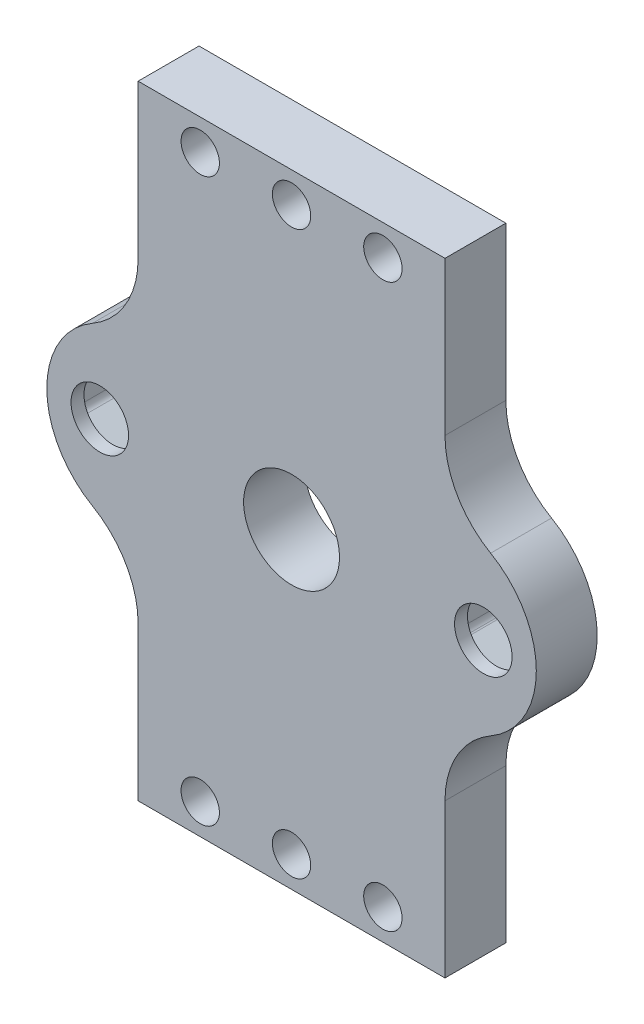
SolidWorks part; units mm, degrees
ref_plane "Front Plane" through (0, 0, 0) normal (0, 0, 1) x (1, 0, 0)
ref_plane "Top Plane" through (0, 0, 0) normal (0, 1, 0) x (1, 0, 0)
ref_plane "Right Plane" through (0, 0, 0) normal (1, 0, 0) x (0, 0, -1)
sketch "Sketch1" plane through (0, 0, 0) normal (0, 0, 1) x (1, 0, 0)
  line L0 (16, 32.5) -> (16, 16.4978)
  line L1 (-16, 16.4978) -> (-16, 32.5)
  line L2 (-16, 32.5) -> (16, 32.5)
  line L3 (16, -32.5) -> (-16, -32.5)
  line L4 (16, -16.4978) -> (16, -32.5)
  line L5 (-16, -32.5) -> (-16, -16.4978)
  arc A0 (20.7625, -8.2489) -> (20.7625, 8.2489) centre (16, 0) ccw
  arc A1 (16, 16.4978) -> (20.7625, 8.2489) centre (25.525, 16.4978) ccw
  circle A2 centre (9.525, 29.325) radius 2
  circle A3 centre (0, 29.325) radius 2
  circle A4 centre (-9.525, 29.325) radius 2
  arc A5 (-20.7625, 8.2489) -> (-16, 16.4978) centre (-25.525, 16.4978) ccw
  arc A6 (20.7625, -8.2489) -> (16, -16.4978) centre (25.525, -16.4978) ccw
  arc A7 (-16, -16.4978) -> (-20.7625, -8.2489) centre (-25.525, -16.4978) ccw
  arc A8 (-20.7625, 8.2489) -> (-20.7625, -8.2489) centre (-16, 0) ccw
  circle A9 centre (-20, 0) radius 3
  circle A10 centre (20, 0) radius 3
  circle A11 centre (0, 0) radius 5
  circle A12 centre (0, -29.325) radius 2
  circle A13 centre (-9.525, -29.325) radius 2
  circle A14 centre (9.525, -29.325) radius 2
extrude "Boss-Extrude1" add sketch "Sketch1" along normal blind 6.35
sketch "Sketch2" plane through (0, 0, 0) normal (0, 0, -1) x (-1, 0, 0)
  line L0 (-24.2999, -1.9872) -> (-24.2999, 1.9857)
  line L1 (-20.4296, -4.7179) -> (-23.8702, -2.7314)
  line L2 (-16.1296, -2.7314) -> (-19.5702, -4.7179)
  line L3 (-15.6999, 1.9857) -> (-15.6999, -1.9872)
  line L4 (-19.5702, 4.7164) -> (-16.1302, 2.7303)
  line L5 (-23.8702, 2.73) -> (-20.4296, 4.7164)
  line L6 (-19.9999, 4.8314) -> (-19.9999, -0.0007) construction
  line L7 (-19.9999, -0.0007) -> (-19.9999, -4.8329) construction
  line L8 (0, 32.5) -> (0, -32.5) construction
  line L9 (16, 32.5) -> (-16, 32.5) construction
  line L10 (-16, -32.5) -> (16, -32.5) construction
  line L11 (15.6999, 1.9857) -> (15.6999, -1.9872)
  line L12 (19.9999, 4.8314) -> (19.9999, -0.0007) construction
  line L13 (19.9999, -0.0007) -> (19.9999, -4.8329) construction
  line L14 (16.1296, -2.7314) -> (19.5702, -4.7179)
  line L15 (20.4296, -4.7179) -> (23.8702, -2.7314)
  line L16 (24.2999, -1.9872) -> (24.2999, 1.9857)
  line L17 (23.8702, 2.73) -> (20.4296, 4.7164)
  line L18 (19.5702, 4.7164) -> (16.1302, 2.7303)
  arc A0 (-15.9999, 2.6381) -> (-16.1302, 2.7303) centre (-16.5633, 1.98) ccw
  arc A1 (15.9999, 2.6381) -> (16.1302, 2.7303) centre (16.5633, 1.98) cw
  spline S0 degree 3 poles (-23.8702, -2.7314) (-23.8703, -2.7314) (-23.8704, -2.7313) (-23.8705, -2.7312) (-23.8915, -2.7191) (-23.9127, -2.7057) (-23.9338, -2.6908) (-24.0382, -2.6176) (-24.1224, -2.5247) (-24.247, -2.3089) (-24.2853, -2.1895) (-24.2966, -2.0626) (-24.2988, -2.0368) (-24.2998, -2.0118) (-24.2999, -1.9875) (-24.2999, -1.9874) (-24.2999, -1.9873) (-24.2999, -1.9872) knots -0.293601 -0.293601 -0.293601 -0.293601 -0.293567 -0.293567 -0.293567 -0.288728 -0.288728 -0.288728 -0.264902 -0.264902 -0.241075 -0.241075 -0.241075 -0.236237 -0.236237 -0.236237 -0.236203 -0.236203 -0.236203 -0.236203 weights 1 1 1 1 1 1 1 1 1 1 1 1 1 1 1 1 1 1
  spline S1 degree 3 poles (-19.5702, -4.7179) (-19.5703, -4.7179) (-19.5704, -4.718) (-19.5705, -4.718) (-19.5915, -4.7301) (-19.6137, -4.7418) (-19.6372, -4.7527) (-19.7527, -4.8064) (-19.8753, -4.8329) (-20.1245, -4.8329) (-20.2471, -4.8064) (-20.3626, -4.7527) (-20.3861, -4.7418) (-20.4083, -4.7301) (-20.4293, -4.718) (-20.4294, -4.718) (-20.4295, -4.7179) (-20.4296, -4.7179) knots -0.293601 -0.293601 -0.293601 -0.293601 -0.293567 -0.293567 -0.293567 -0.288728 -0.288728 -0.288728 -0.264902 -0.264902 -0.241075 -0.241075 -0.241075 -0.236237 -0.236237 -0.236237 -0.236203 -0.236203 -0.236203 -0.236203 weights 1 1 1 1 1 1 1 1 1 1 1 1 1 1 1 1 1 1
  spline S2 degree 3 poles (-15.6999, -1.9872) (-15.6999, -1.9873) (-15.6999, -1.9874) (-15.6999, -1.9875) (-15.7, -2.0118) (-15.701, -2.0368) (-15.7032, -2.0626) (-15.7145, -2.1895) (-15.7528, -2.3089) (-15.8637, -2.5009) (-15.9255, -2.5759) (-15.9999, -2.6396) knots -0.293601 -0.293601 -0.293601 -0.293601 -0.293567 -0.293567 -0.293567 -0.288728 -0.288728 -0.288728 -0.264902 -0.264902 -0.246329 -0.246329 -0.246329 -0.246329 weights 1 1 1 1 1 1 1 1 1 1 1 1
  spline S3 degree 3 poles (-15.9999, 2.6381) (-15.9255, 2.5745) (-15.8637, 2.4994) (-15.7528, 2.3075) (-15.7145, 2.1881) (-15.7032, 2.0611) (-15.701, 2.0354) (-15.7, 2.0103) (-15.6999, 1.9861) (-15.6999, 1.9859) (-15.6999, 1.9858) (-15.6999, 1.9857) knots -0.283475 -0.283475 -0.283475 -0.283475 -0.264902 -0.264902 -0.241075 -0.241075 -0.241075 -0.236237 -0.236237 -0.236237 -0.236203 -0.236203 -0.236203 -0.236203 weights 1 1 1 1 1 1 1 1 1 1 1 1
  spline S4 degree 3 poles (-20.4296, 4.7164) (-20.4295, 4.7165) (-20.4294, 4.7165) (-20.4293, 4.7166) (-20.4083, 4.7287) (-20.3861, 4.7403) (-20.3626, 4.7512) (-20.2471, 4.805) (-20.1245, 4.8314) (-19.8753, 4.8314) (-19.7527, 4.805) (-19.6372, 4.7512) (-19.6137, 4.7403) (-19.5915, 4.7287) (-19.5705, 4.7166) (-19.5704, 4.7165) (-19.5703, 4.7165) (-19.5702, 4.7164) knots -0.293601 -0.293601 -0.293601 -0.293601 -0.293567 -0.293567 -0.293567 -0.288728 -0.288728 -0.288728 -0.264902 -0.264902 -0.241075 -0.241075 -0.241075 -0.236237 -0.236237 -0.236237 -0.236203 -0.236203 -0.236203 -0.236203 weights 1 1 1 1 1 1 1 1 1 1 1 1 1 1 1 1 1 1
  spline S5 degree 3 poles (-24.2999, 1.9857) (-24.2999, 1.9858) (-24.2999, 1.9859) (-24.2999, 1.9861) (-24.2998, 2.0103) (-24.2988, 2.0354) (-24.2966, 2.0611) (-24.2853, 2.1881) (-24.247, 2.3075) (-24.1224, 2.5232) (-24.0382, 2.6162) (-23.9338, 2.6894) (-23.9127, 2.7042) (-23.8915, 2.7176) (-23.8705, 2.7298) (-23.8704, 2.7298) (-23.8703, 2.7299) (-23.8702, 2.73) knots -0.293601 -0.293601 -0.293601 -0.293601 -0.293567 -0.293567 -0.293567 -0.288728 -0.288728 -0.288728 -0.264902 -0.264902 -0.241075 -0.241075 -0.241075 -0.236237 -0.236237 -0.236237 -0.236203 -0.236203 -0.236203 -0.236203 weights 1 1 1 1 1 1 1 1 1 1 1 1 1 1 1 1 1 1
  spline S6 degree 3 poles (-15.9999, -2.6396) (-16.0209, -2.6576) (-16.043, -2.6747) (-16.066, -2.6908) (-16.0871, -2.7057) (-16.1083, -2.7191) (-16.1293, -2.7312) (-16.1294, -2.7313) (-16.1295, -2.7314) (-16.1296, -2.7314) knots -0.246329 -0.246329 -0.246329 -0.246329 -0.241075 -0.241075 -0.241075 -0.236237 -0.236237 -0.236237 -0.236203 -0.236203 -0.236203 -0.236203 weights 1 1 1 1 1 1 1 1 1 1
  spline S7 degree 3 poles (15.6999, -1.9872) (15.6999, -1.9873) (15.6999, -1.9874) (15.6999, -1.9875) (15.7, -2.0118) (15.701, -2.0368) (15.7032, -2.0626) (15.7145, -2.1895) (15.7528, -2.3089) (15.8637, -2.5009) (15.9255, -2.5759) (15.9999, -2.6396) knots -0.293601 -0.293601 -0.293601 -0.293601 -0.293567 -0.293567 -0.293567 -0.288728 -0.288728 -0.288728 -0.264902 -0.264902 -0.246329 -0.246329 -0.246329 -0.246329 weights 1 1 1 1 1 1 1 1 1 1 1 1
  spline S8 degree 3 poles (15.9999, -2.6396) (16.0209, -2.6576) (16.043, -2.6747) (16.066, -2.6908) (16.0871, -2.7057) (16.1083, -2.7191) (16.1293, -2.7312) (16.1294, -2.7313) (16.1295, -2.7314) (16.1296, -2.7314) knots -0.246329 -0.246329 -0.246329 -0.246329 -0.241075 -0.241075 -0.241075 -0.236237 -0.236237 -0.236237 -0.236203 -0.236203 -0.236203 -0.236203 weights 1 1 1 1 1 1 1 1 1 1
  spline S9 degree 3 poles (15.9999, 2.6381) (15.9255, 2.5745) (15.8637, 2.4994) (15.7528, 2.3075) (15.7145, 2.1881) (15.7032, 2.0611) (15.701, 2.0354) (15.7, 2.0103) (15.6999, 1.9861) (15.6999, 1.9859) (15.6999, 1.9858) (15.6999, 1.9857) knots -0.283475 -0.283475 -0.283475 -0.283475 -0.264902 -0.264902 -0.241075 -0.241075 -0.241075 -0.236237 -0.236237 -0.236237 -0.236203 -0.236203 -0.236203 -0.236203 weights 1 1 1 1 1 1 1 1 1 1 1 1
  spline S10 degree 3 poles (19.5702, -4.7179) (19.5703, -4.7179) (19.5704, -4.718) (19.5705, -4.718) (19.5915, -4.7301) (19.6137, -4.7418) (19.6372, -4.7527) (19.7527, -4.8064) (19.8753, -4.8329) (20.1245, -4.8329) (20.2471, -4.8064) (20.3626, -4.7527) (20.3861, -4.7418) (20.4083, -4.7301) (20.4293, -4.718) (20.4294, -4.718) (20.4295, -4.7179) (20.4296, -4.7179) knots -0.293601 -0.293601 -0.293601 -0.293601 -0.293567 -0.293567 -0.293567 -0.288728 -0.288728 -0.288728 -0.264902 -0.264902 -0.241075 -0.241075 -0.241075 -0.236237 -0.236237 -0.236237 -0.236203 -0.236203 -0.236203 -0.236203 weights 1 1 1 1 1 1 1 1 1 1 1 1 1 1 1 1 1 1
  spline S11 degree 3 poles (23.8702, -2.7314) (23.8703, -2.7314) (23.8704, -2.7313) (23.8705, -2.7312) (23.8915, -2.7191) (23.9127, -2.7057) (23.9338, -2.6908) (24.0382, -2.6176) (24.1224, -2.5247) (24.247, -2.3089) (24.2853, -2.1895) (24.2966, -2.0626) (24.2988, -2.0368) (24.2998, -2.0118) (24.2999, -1.9875) (24.2999, -1.9874) (24.2999, -1.9873) (24.2999, -1.9872) knots -0.293601 -0.293601 -0.293601 -0.293601 -0.293567 -0.293567 -0.293567 -0.288728 -0.288728 -0.288728 -0.264902 -0.264902 -0.241075 -0.241075 -0.241075 -0.236237 -0.236237 -0.236237 -0.236203 -0.236203 -0.236203 -0.236203 weights 1 1 1 1 1 1 1 1 1 1 1 1 1 1 1 1 1 1
  spline S12 degree 3 poles (24.2999, 1.9857) (24.2999, 1.9858) (24.2999, 1.9859) (24.2999, 1.9861) (24.2998, 2.0103) (24.2988, 2.0354) (24.2966, 2.0611) (24.2853, 2.1881) (24.247, 2.3075) (24.1224, 2.5232) (24.0382, 2.6162) (23.9338, 2.6894) (23.9127, 2.7042) (23.8915, 2.7176) (23.8705, 2.7298) (23.8704, 2.7298) (23.8703, 2.7299) (23.8702, 2.73) knots -0.293601 -0.293601 -0.293601 -0.293601 -0.293567 -0.293567 -0.293567 -0.288728 -0.288728 -0.288728 -0.264902 -0.264902 -0.241075 -0.241075 -0.241075 -0.236237 -0.236237 -0.236237 -0.236203 -0.236203 -0.236203 -0.236203 weights 1 1 1 1 1 1 1 1 1 1 1 1 1 1 1 1 1 1
  spline S13 degree 3 poles (20.4296, 4.7164) (20.4295, 4.7165) (20.4294, 4.7165) (20.4293, 4.7166) (20.4083, 4.7287) (20.3861, 4.7403) (20.3626, 4.7512) (20.2471, 4.805) (20.1245, 4.8314) (19.8753, 4.8314) (19.7527, 4.805) (19.6372, 4.7512) (19.6137, 4.7403) (19.5915, 4.7287) (19.5705, 4.7166) (19.5704, 4.7165) (19.5703, 4.7165) (19.5702, 4.7164) knots -0.293601 -0.293601 -0.293601 -0.293601 -0.293567 -0.293567 -0.293567 -0.288728 -0.288728 -0.288728 -0.264902 -0.264902 -0.241075 -0.241075 -0.241075 -0.236237 -0.236237 -0.236237 -0.236203 -0.236203 -0.236203 -0.236203 weights 1 1 1 1 1 1 1 1 1 1 1 1 1 1 1 1 1 1
  point P15 (-19.9999, -0.0007)
  point P16 (19.9999, -0.0007)
  dimension "D1" = 4.3
  dimension "D2" = 4.3
  dimension "D3" = 4.8322
  dimension "D4" = 4.8322
extrude "Cut-Extrude1" cut sketch "Sketch2" against normal blind 5
